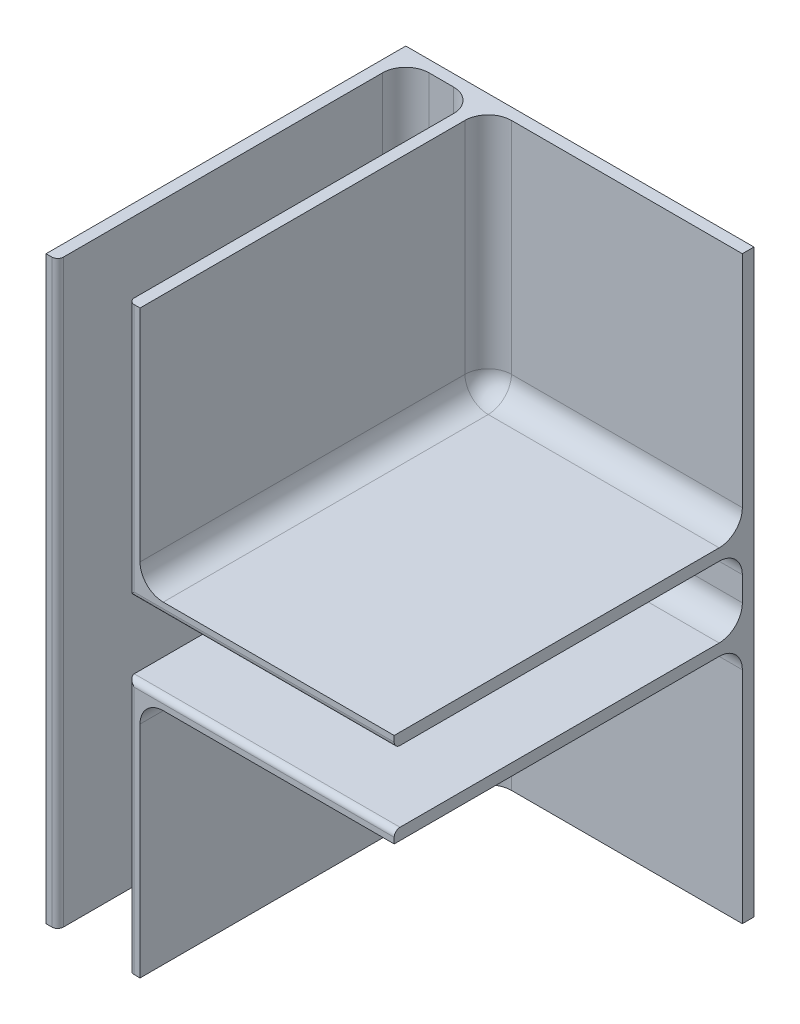
SolidWorks part; units mm, degrees
ref_plane "Front" through (0, 0, 0) normal (0, 0, 1) x (1, 0, 0)
ref_plane "Top" through (0, 0, 0) normal (0, 1, 0) x (1, 0, 0)
ref_plane "Right" through (0, 0, 0) normal (1, 0, 0) x (0, 0, -1)
sketch "Sketch1" plane through (0, 0, 0) normal (0, 0, 1) x (1, 0, 0)
  line L5 (0, 0) -> (30, 0)
  line L6 (0, 0) -> (0, 50)
  line L7 (0, 50) -> (30, 50)
  line L8 (30, 0) -> (30, 50)
  dimension "D1" = 50
  dimension "D2" = 30
extrude "Boss-Extrude1" add sketch "Sketch1" along normal blind 1
sketch "Sketch2" plane through (0, 0, 1) normal (0, 0, 1) x (1, 0, 0)
  line L0 (30, 50) -> (0, 50) construction
  line L5 (7.1, 0) -> (8.1, 0)
  line L25 (0, 50) -> (1, 50)
  line L26 (0, 50) -> (0, 0)
  line L27 (0, 0) -> (1, 0)
  line L28 (1, 50) -> (1, 0)
  line L29 (0, 0) -> (30, 0) construction
  line L30 (7.1, 0) -> (7.1, 21.95)
  line L31 (7.1, 21.95) -> (8.1, 21.95)
  line L32 (8.1, 0) -> (8.1, 20.95)
  line L33 (7.1, 50) -> (8.1, 50)
  line L34 (7.1, 50) -> (7.1, 28.05)
  line L35 (7.1, 28.05) -> (8.1, 28.05)
  line L36 (8.1, 50) -> (8.1, 29.05)
  line L38 (8.1, 28.05) -> (30, 28.05)
  line L40 (8.1, 29.05) -> (30, 29.05)
  line L41 (30, 28.05) -> (30, 29.05)
  line L42 (30, 0) -> (30, 50) construction
  line L44 (8.1, 21.95) -> (30, 21.95)
  line L46 (8.1, 20.95) -> (30, 20.95)
  line L47 (30, 21.95) -> (30, 20.95)
  dimension "D1" = 6.1
  dimension "D2" = 1
  dimension "D3" = 6.1
extrude "Boss-Extrude2" add sketch "Sketch2" along normal blind 30
fillet "Fillet4" radius 2 11 edges at (7.1, 39.025, 1) (8.1, 29.05, 16) (1, 25, 1) (7.1, 10.975, 1) (8.1, 39.525, 1) (19.05, 29.05, 1) (18.55, 21.95, 1) (18.55, 28.05, 1) (8.1, 20.95, 16) (8.1, 10.475, 1) (19.05, 20.95, 1)
fillet "Fillet5" radius 0.5 5 edges at (1, 25, 31) (7.1, 10.975, 31) (18.55, 21.95, 31) (18.55, 28.05, 31) (7.1, 39.025, 31)
